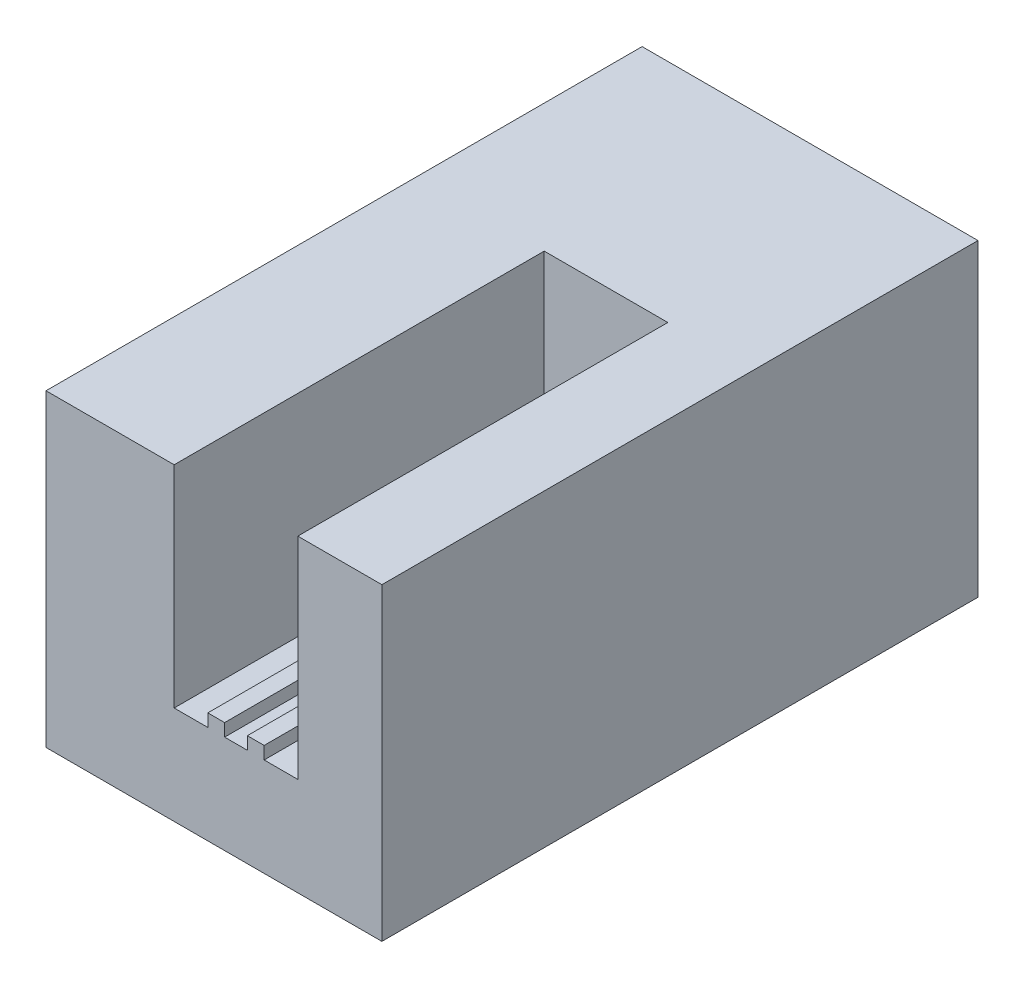
SolidWorks part; units mm, degrees
ref_plane "Piano frontale" through (0, 0, 0) normal (0, 0, 1) x (1, 0, 0)
ref_plane "Piano superiore" through (0, 0, 0) normal (0, 1, 0) x (1, 0, 0)
ref_plane "Piano destro" through (0, 0, 0) normal (1, 0, 0) x (0, 0, -1)
sketch "Schizzo1" plane through (0, 0, 0) normal (0, 0, 1) x (1, 0, 0)
  line L1 (0, 0) -> (3994, 0)
  line L2 (0, 0) -> (0, 3673.5)
  line L3 (0, 3673.5) -> (3994, 3673.5)
  line L4 (3994, 0) -> (3994, 3673.5)
  dimension "D1" = 3994
  dimension "D2" = 3673.5
extrude "Estrusione-Estrusione1" add sketch "Schizzo1" against normal blind 7088
sketch "Schizzo2" plane through (0, 0, 0) normal (0, 0, 1) x (1, 0, 0)
  line L0 (3994, 2436.8171) -> (2994, 2436.8171) construction
  line L1 (3994, 0) -> (3994, 3673.5) construction
  line L2 (2994, 0) -> (2994, 1318.5) construction
  line L3 (0, 0) -> (3994, 0) construction
  line L4 (3994, 3673.5) -> (0, 3673.5) construction
  line L5 (2994, 1318.5) -> (1524, 1318.5)
  line L6 (2994, 1318.5) -> (2994, 3673.5)
  line L7 (2994, 3673.5) -> (1524, 3673.5)
  line L8 (1524, 1318.5) -> (1524, 3673.5)
  dimension "D1" = 1000
  dimension "D2" = 1318.5
  dimension "D3" = 1470
extrude "Taglio-Estrusione1" cut sketch "Schizzo2" against normal blind 4400
sketch "Schizzo3" plane through (0, 1318.5, 0) normal (0, 1, 0) x (1, 0, 0)
  line L1 (1924, 0) -> (2124, 0)
  line L2 (1924, 0) -> (1924, 4400)
  line L3 (1924, 4400) -> (2124, 4400)
  line L4 (1524, 0) -> (2994, 0)
  line L5 (2994, 0) -> (2994, 4400)
  line L6 (2994, 4400) -> (1524, 4400)
  line L7 (1524, 4400) -> (1524, 0)
  line L8 (1524, 0) -> (2994, 0)
  line L9 (2994, 0) -> (2994, 4400)
  line L10 (2994, 4400) -> (1524, 4400)
  line L11 (1524, 4400) -> (1524, 0)
  line L12 (2124, 0) -> (2124, 4400)
  line L13 (1924, 0) -> (2124, 4400) construction
  line L14 (1924, 4400) -> (2124, 0) construction
  line L15 (2394, 0) -> (2594, 0)
  line L16 (2394, 0) -> (2394, 4400)
  line L17 (2394, 4400) -> (2594, 4400)
  line L18 (2594, 0) -> (2594, 4400)
  line L19 (2394, 0) -> (2594, 4400) construction
  line L20 (2394, 4400) -> (2594, 0) construction
  point P2 (2024, 2200)
  point P9 (2494, 2200)
  point P14 (0, 0)
  line M13 (1524, 0) -> (2994, 0)
  line M14 (2994, 0) -> (2994, 4400)
  line M15 (2994, 4400) -> (1524, 4400)
  line M16 (1524, 4400) -> (1524, 0)
  dimension "D2" = 400
  dimension "D3" = 400
  dimension "D4" = 200
  dimension "D1" = 0
extrude "Taglio-Estrusione2" cut sketch "Schizzo3" against normal blind 150 contours L2 M13 M15 M16 | L16 L10 L12 M13 | L18 M13 M14 M15
